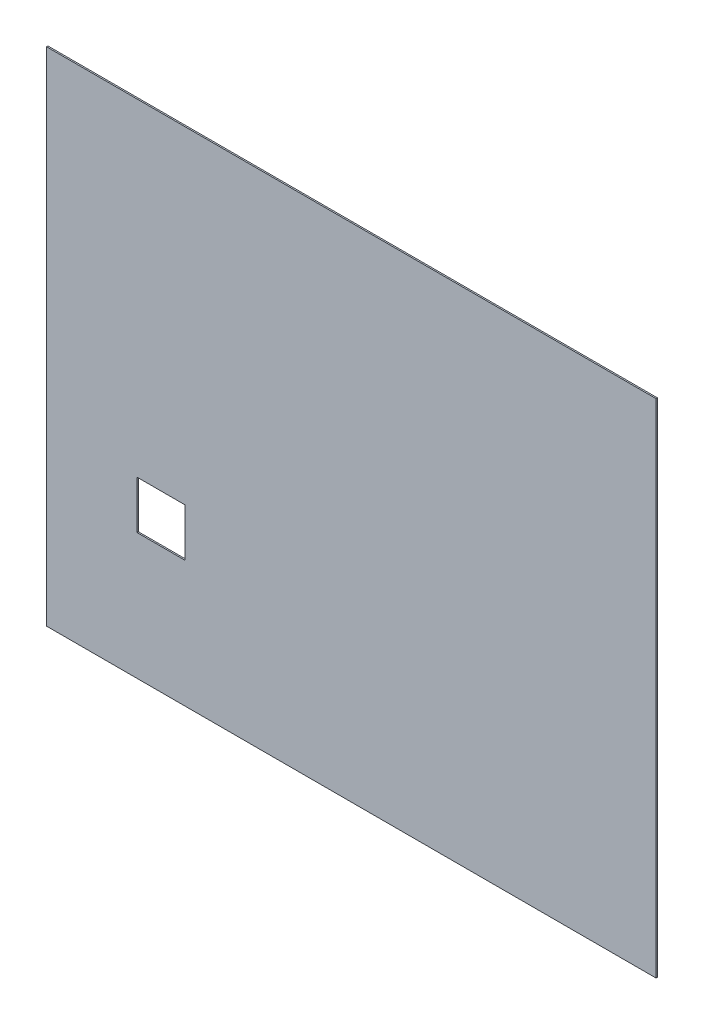
SolidWorks part; units mm, degrees
ref_plane "Front Plane" through (0, 0, 0) normal (0, 0, 1) x (1, 0, 0)
ref_plane "Top Plane" through (0, 0, 0) normal (0, 1, 0) x (1, 0, 0)
ref_plane "Right Plane" through (0, 0, 0) normal (1, 0, 0) x (0, 0, -1)
sketch "Sketch1" plane through (0, 0, 0) normal (0, 0, 1) x (1, 0, 0)
  line L1 (-215.9, -177.8) -> (215.9, -177.8)
  line L2 (-215.9, -177.8) -> (-215.9, 177.8)
  line L3 (-215.9, 177.8) -> (215.9, 177.8)
  line L4 (215.9, -177.8) -> (215.9, 177.8)
  line L5 (-215.9, -177.8) -> (215.9, 177.8) construction
  line L6 (-215.9, 177.8) -> (215.9, -177.8) construction
  point P0 (0, 0)
  dimension "D1" = 355.6
  dimension "D2" = 431.8
extrude "Boss-Extrude1" add sketch "Sketch1" along normal blind 0.9906
sketch "Sketch2" plane through (0, 0, 0.9906) normal (0, 0, 1) x (1, 0, 0)
  line L0 (-215.9, 177.8) -> (-215.9, -177.8) construction
  line L1 (-215.9, -177.8) -> (215.9, -177.8) construction
  line L4 (-151.9, -88.3) -> (-117.9, -88.3)
  line L5 (-151.9, -88.3) -> (-151.9, -54.3)
  line L6 (-151.9, -54.3) -> (-117.9, -54.3)
  line L7 (-117.9, -88.3) -> (-117.9, -54.3)
  line L8 (-151.9, -88.3) -> (-117.9, -54.3) construction
  line L9 (-151.9, -54.3) -> (-117.9, -88.3) construction
  point P6 (-134.9, -71.3)
  dimension "D1" = 64
  dimension "D2" = 89.5
  dimension "D3" = 34
  dimension "D4" = 34
extrude "Cut-Extrude1" cut sketch "Sketch2" against normal through all
sketch "Sketch3" plane through (0, 0, 0) normal (0, 0, -1) x (-1, 0, 0)
  circle A0 centre (-152.6044, 148.5814) radius 16.8118
  circle A1 centre (178.9323, 148.5814) radius 17.9404
  circle A2 centre (-176.007, -138.1003) radius 16.8118
  circle A3 centre (178.9323, -142.4883) radius 15.9185
extrude "Boss-Extrude2" add sketch "Sketch3" along normal blind 7.62
sketch "Sketch4" plane through (0, 0, 0.9906) normal (0, 0, 1) x (1, 0, 0)
  circle A0 centre (-151.9, -54.3) radius 1.5875
  circle A1 centre (-117.9, -54.3) radius 1.5875
  circle A2 centre (-117.9, -88.3) radius 1.5875
  circle A3 centre (-151.9, -88.3) radius 1.5875
  dimension "D1" = 3.175
extrude "Cut-Extrude2" [suppressed] cut sketch "Sketch4" against normal through all
